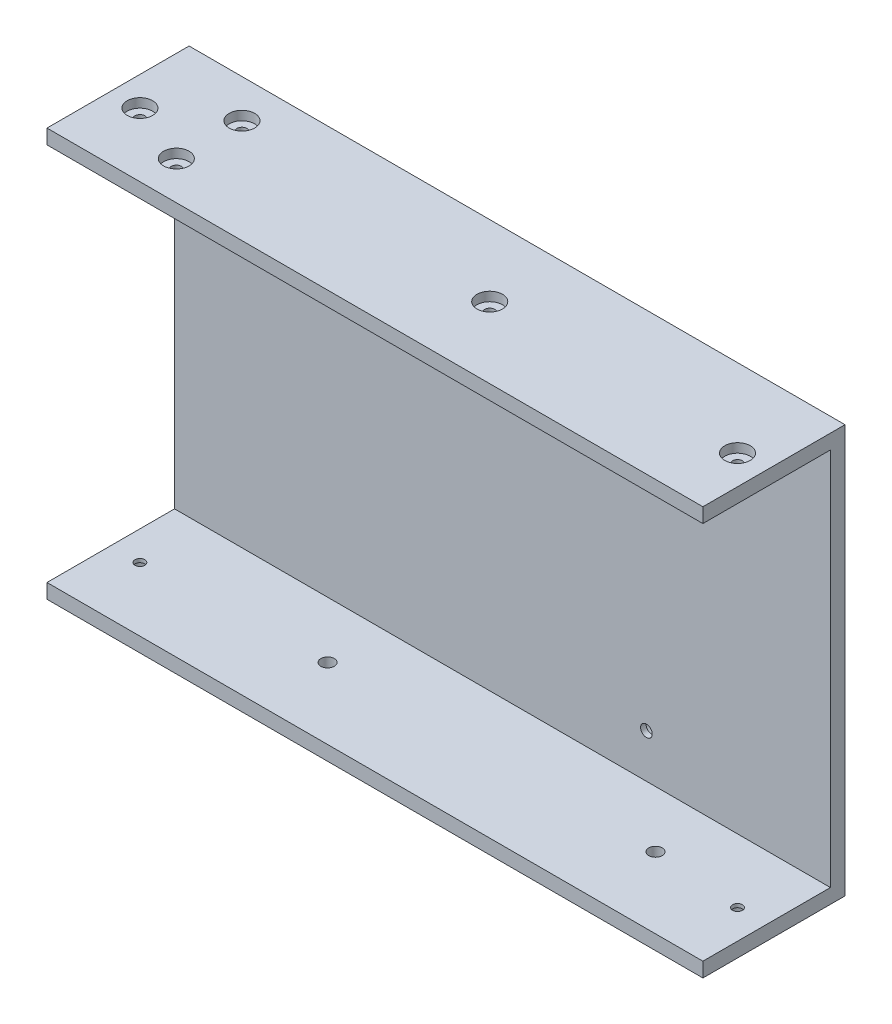
SolidWorks part; units mm, degrees
material "PET"
ref_plane "Přední rovina" through (0, 0, 0) normal (0, 0, 1) x (1, 0, 0)
ref_plane "Horní rovina" through (0, 0, 0) normal (0, 1, 0) x (1, 0, 0)
ref_plane "Pravá rovina" through (0, 0, 0) normal (1, 0, 0) x (0, 0, -1)
sketch "Skica1" plane through (0, 0, 0) normal (0, 0, 1) x (1, 0, 0)
  line L0 (-64.5, 0) -> (64.5, 0) construction
  line L1 (-64.5, -48.5) -> (64.5, -48.5) construction
  line L2 (-64.5, -48.5) -> (-64.5, 48.5) construction
  line L3 (-64.5, 48.5) -> (64.5, 48.5) construction
  line L4 (64.5, -48.5) -> (64.5, 48.5) construction
  line L5 (-64.5, -48.5) -> (64.5, 48.5) construction
  line L6 (-64.5, 48.5) -> (64.5, -48.5) construction
  line L8 (-69.5, -59.5) -> (110.5, -59.5)
  line L9 (-69.5, -59.5) -> (-69.5, 52.5)
  line L10 (-69.5, 52.5) -> (110.5, 52.5)
  line L11 (110.5, -59.5) -> (110.5, 52.5)
  line L12 (-69.5, -59.5) -> (110.5, 52.5) construction
  line L13 (-69.5, 52.5) -> (110.5, -59.5) construction
  point P0 (0, 0)
  point P8 (26.125, 0)
  dimension "D1" = 97
  dimension "D2" = 129
  dimension "D3" = 180
  dimension "D4" = 112
  dimension "D5" = 5
  dimension "D6" = 4
extrude "Přidat vysunutím1" add sketch "Skica1" along normal blind 4
sketch "Skica3" plane through (0, 0, 4) normal (0, 0, 1) x (1, 0, 0)
  line L0 (110.5, -59.5) -> (110.5, 52.5) construction
  line L1 (-69.5, 52.5) -> (110.5, 52.5)
  line L2 (-69.5, 52.5) -> (-69.5, 48.5)
  line L3 (-69.5, 48.5) -> (110.5, 48.5)
  line L4 (110.5, 52.5) -> (110.5, 48.5)
  line L5 (-69.5, 52.5) -> (110.5, 48.5) construction
  line L6 (-69.5, 48.5) -> (110.5, 52.5) construction
  line L8 (-69.5, -59.5) -> (110.5, -59.5)
  line L9 (-69.5, -59.5) -> (-69.5, -55.5)
  line L10 (-69.5, -55.5) -> (110.5, -55.5)
  line L11 (110.5, -59.5) -> (110.5, -55.5)
  line L12 (-69.5, -59.5) -> (110.5, -55.5) construction
  line L13 (-69.5, -55.5) -> (110.5, -59.5) construction
  point P4 (20.5, 50.5)
  point P12 (20.5, -57.5)
  dimension "D1" = 4
  dimension "D2" = 4
extrude "Přidat vysunutím2" add sketch "Skica3" along normal blind 35
sketch "Skica4" plane through (0, 52.5, 0) normal (0, 1, 0) x (1, 0, 0)
  line L0 (-69.5, -19.5) -> (110.5, -19.5) construction
  line L1 (-69.5, -39) -> (-69.5, 0) construction
  line L2 (110.5, -39) -> (110.5, 0) construction
  line L3 (-44.5, -4.5) -> (-44.5, -34.5) construction
  line L4 (64.5, -34.5) -> (-64.5, -34.5) construction
  line L5 (64.5, -34.5) -> (64.5, -4.5) construction
  line L6 (64.5, -4.5) -> (-64.5, -4.5) construction
  line L7 (-64.5, -34.5) -> (-64.5, -4.5) construction
  line L8 (64.5, -34.5) -> (-64.5, -4.5) construction
  line L9 (64.5, -4.5) -> (-64.5, -34.5) construction
  circle A0 centre (32.5, -19.5) radius 1.35
  circle A1 centre (-44.5, -10.5) radius 1.35
  circle A2 centre (-44.5, -28.5) radius 1.35
  point P6 (0, -19.5)
  dimension "D4" = 32
  dimension "D5" = 2.7
  dimension "D6" = 20
  dimension "D9" = 2.7
  dimension "D10" = 2.7
  dimension "D1" = 30
  dimension "D2" = 129
  dimension "D3" = 5
  dimension "D7" = 6
  dimension "D8" = 18
extrude "Odebrat vysunutím1" cut sketch "Skica4" against normal up to surface (4 mm away) up to face at (20.5, 48.5, 21.5)
sketch "Skica6" plane through (0, -59.5, 0) normal (0, -1, 0) x (1, 0, 0)
  line L0 (-69.5, 21.5) -> (110.5, 21.5) construction
  line L1 (110.5, 39) -> (110.5, 0) construction
  line L2 (-69.5, 39) -> (-69.5, 0) construction
  line L3 (-69.5, 39) -> (110.5, 39) construction
  circle A0 centre (102.5, 21.5) radius 1.35
  circle A1 centre (-61.5, 21.5) radius 1.35
  dimension "D2" = 2.7
  dimension "D3" = 2.7
  dimension "D1" = 17.5
  dimension "D4" = 8
  dimension "D5" = 8
extrude "Odebrat vysunutím2" cut sketch "Skica6" against normal up to surface (112 mm away) up to face at (32.5, 52.5, 20.85)
sketch "Skica7" plane through (0, -59.5, 0) normal (0, -1, 0) x (1, 0, 0)
  circle A0 centre (-61.5, 21.5) radius 3.5
  circle A1 centre (102.5, 21.5) radius 3.5
  dimension "D1" = 7
  dimension "D2" = 7
extrude "Odebrat vysunutím3" cut sketch "Skica7" against normal blind 3
sketch "Skica8" plane through (0, -59.5, 0) normal (0, -1, 0) x (1, 0, 0)
  line L0 (-69.5, 19.5) -> (110.5, 19.5) construction
  line L1 (-69.5, 39) -> (-69.5, 0) construction
  line L2 (110.5, 39) -> (110.5, 0) construction
  line L3 (20.5, 39) -> (20.5, 0) construction
  line L4 (-69.5, 39) -> (110.5, 39) construction
  line L5 (-69.5, 0) -> (110.5, 0) construction
  circle A0 centre (-12, 19.5) radius 1.85
  circle A1 centre (78, 19.5) radius 1.85
  dimension "D1" = 3.7
  dimension "D2" = 3.7
  dimension "D3" = 90
  dimension "D4" = 32.5
extrude "Odebrat vysunutím4" cut sketch "Skica8" against normal up to surface (4 mm away) up to face at (102.5, -55.5, 20.15)
sketch "Skica9" plane through (0, 52.5, 0) normal (0, 1, 0) x (1, 0, 0)
  circle A0 centre (-61.5, -21.5) radius 3.5
  circle A1 centre (-44.5, -10.5) radius 3.5
  circle A2 centre (-44.5, -28.5) radius 3.5
  circle A3 centre (32.5, -19.5) radius 3.5
  circle A4 centre (102.5, -21.5) radius 3.5
  dimension "D1" = 7
  dimension "D2" = 7
  dimension "D3" = 7
  dimension "D4" = 7
  dimension "D5" = 7
extrude "Odebrat vysunutím5" cut sketch "Skica9" against normal blind 2.5
sketch "Skica10" plane through (0, 0, 0) normal (0, 0, -1) x (-1, 0, 0)
  line L1 (69.5, -59.5) -> (-110.5, -59.5) construction
  line L2 (69.5, 52.5) -> (69.5, -59.5) construction
  circle A0 centre (-60, -43.5) radius 1.6
  dimension "D1" = 129.5
  dimension "D3" = 3.2
  dimension "D2" = 16
extrude "Odebrat vysunutím6" cut sketch "Skica10" against normal up to surface (4 mm away) up to face at (20.5, -3.5, 4)
sketch "Skica11" plane through (0, 0, 0) normal (0, 0, -1) x (-1, 0, 0)
  circle A0 centre (-60, -43.5) radius 3.5
  dimension "D1" = 7
extrude "Odebrat vysunutím7" cut sketch "Skica11" against normal blind 2.5
